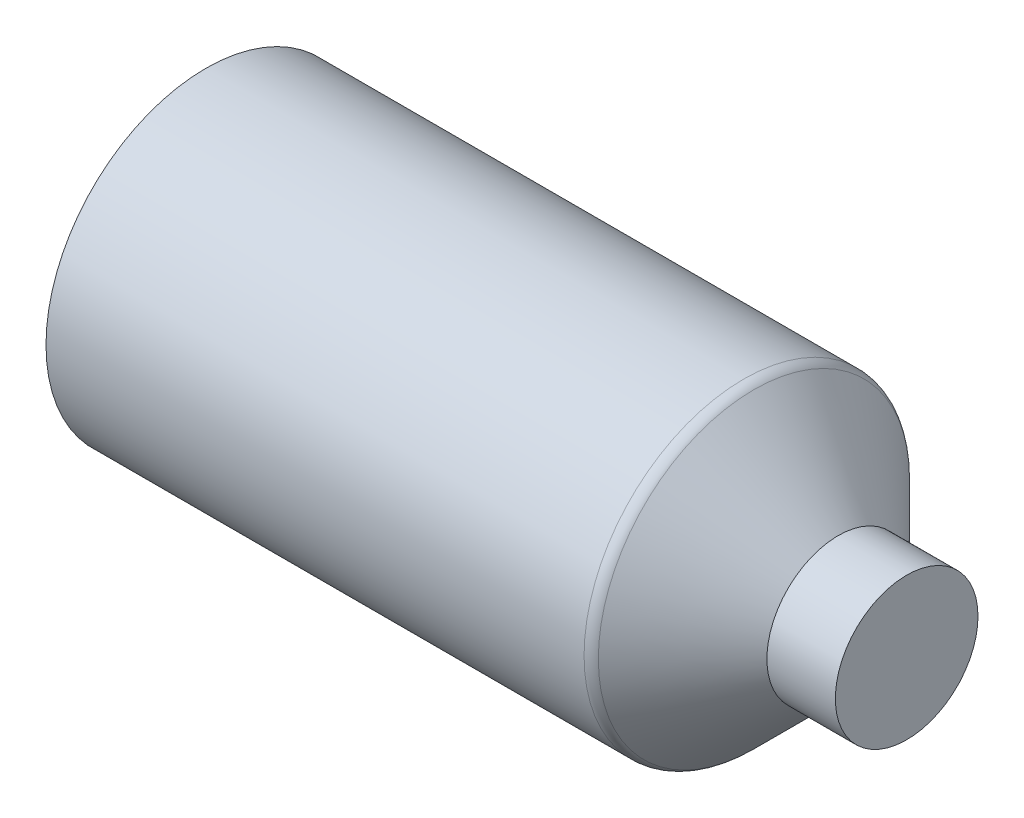
SolidWorks part; units mm, degrees
ref_plane "Front Plane" through (0, 0, 0) normal (0, 0, 1) x (1, 0, 0)
ref_plane "Top Plane" through (0, 0, 0) normal (0, 1, 0) x (1, 0, 0)
ref_plane "Right Plane" through (0, 0, 0) normal (1, 0, 0) x (0, 0, -1)
sketch "Sketch3" plane through (0, 0, 0) normal (0, 0, 1) x (1, 0, 0)
  line L0 (1.7986, 24.13) -> (-76.2, 24.13) construction
  line L1 (-76.2, 17.78) -> (-76.2, 11.43)
  line L2 (-76.2, 24.13) -> (-76.2, 17.78) construction
  line L3 (-76.2, 17.78) -> (-16.3214, 17.78)
  line L4 (-15.1989, 17.315) -> (-5.8214, 7.9375)
  line L5 (-5.8214, 7.9375) -> (-5.8214, -7.9375) construction
  line L6 (-5.8214, 12.7) -> (-5.8214, -12.7) construction
  line L9 (1.7986, 24.1554) -> (1.7986, -24.1554) construction
  line L10 (1.7986, 0) -> (1.7986, 24.13) construction
  line L11 (24.1721, 0) -> (-63.4646, 0) construction
  line L12 (-76.2, 11.43) -> (-15.6639, 11.43)
  line L13 (-15.6639, 11.43) -> (-15.6639, 0)
  line L14 (-15.6639, 0) -> (-5.8214, 0)
  line L15 (-5.8214, 0) -> (-5.8214, 7.9375) construction
  line L16 (-15.6639, 17.78) -> (-15.6639, 11.43) construction
  line L18 (1.7986, 0) -> (-5.8214, 0)
  line L19 (-5.8214, 7.9375) -> (1.7986, 7.9375)
  line L20 (1.7986, 7.9375) -> (1.7986, 0)
  arc A0 (-16.3214, 17.78) -> (-15.1989, 17.315) centre (-16.3214, 16.1925) cw
  dimension "D7" = 1.5875
  dimension "D1" = 45
  dimension "D3" = 6.35
  dimension "D4" = 24.13
  dimension "D5" = 15.875
  dimension "D6" = 76.2
  dimension "D8" = 6.35
revolve "Revolve1" add sketch "Sketch3" angle 360 about L11
